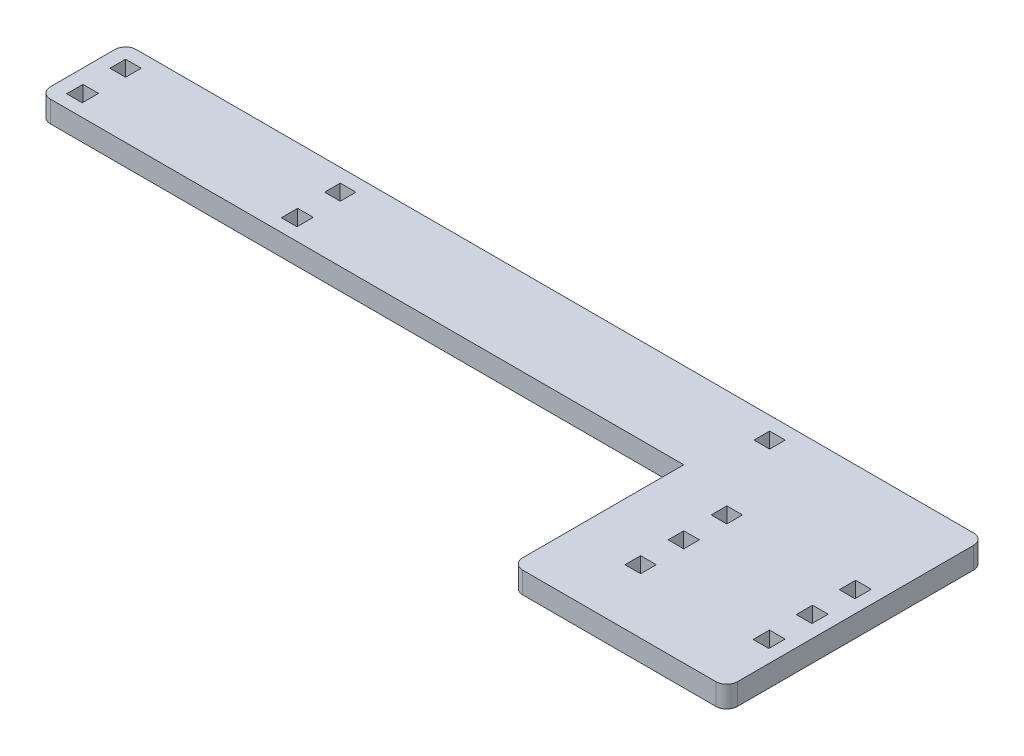
SolidWorks part; units mm, degrees
ref_plane "Front Plane" through (0, 0, 0) normal (0, 0, 1) x (1, 0, 0)
ref_plane "Top Plane" through (0, 0, 0) normal (0, 1, 0) x (1, 0, 0)
ref_plane "Right Plane" through (0, 0, 0) normal (1, 0, 0) x (0, 0, -1)
sketch "Sketch1" plane through (0, 0, 0) normal (0, 1, 0) x (1, 0, 0)
  line L0 (0, 0) -> (254, 0)
  line L1 (254, 0) -> (254, -76.2)
  line L2 (254, -76.2) -> (190.5, -76.2)
  line L3 (190.5, -76.2) -> (190.5, -25.4)
  line L4 (190.5, -25.4) -> (0, -25.4)
  line L5 (0, -25.4) -> (0, 0)
  line L6 (4.211, -16.8148) -> (8.8338, -16.8148)
  line L7 (4.064, -4.064) -> (8.6868, -4.064)
  line L8 (4.064, -4.064) -> (4.064, -8.6868)
  line L9 (4.064, -8.6868) -> (8.6868, -8.6868)
  line L10 (8.6868, -4.064) -> (8.6868, -8.6868)
  line L11 (4.211, -16.8148) -> (4.211, -21.6346)
  line L12 (4.211, -21.6346) -> (8.8338, -21.6346)
  line L13 (8.8338, -16.8148) -> (8.8338, -21.6346)
  line L14 (67.564, -4.064) -> (67.564, -8.6868)
  line L15 (67.564, -4.064) -> (72.1868, -4.064)
  line L16 (72.1868, -4.064) -> (72.1868, -8.6868)
  line L17 (67.564, -8.6868) -> (72.1868, -8.6868)
  line L18 (67.711, -16.8148) -> (72.3338, -16.8148)
  line L19 (72.3338, -16.8148) -> (72.3338, -21.6346)
  line L20 (67.711, -21.6346) -> (72.3338, -21.6346)
  line L21 (67.711, -16.8148) -> (67.711, -21.6346)
  line L30 (194.564, -4.064) -> (194.564, -8.6868)
  line L31 (194.564, -4.064) -> (199.1868, -4.064)
  line L32 (199.1868, -4.064) -> (199.1868, -8.6868)
  line L33 (194.564, -8.6868) -> (199.1868, -8.6868)
  line L46 (131.211, -16.8148) -> (135.8338, -16.8148) [skipped]
  line L47 (135.8338, -16.8148) -> (135.8338, -21.6346) [skipped]
  line L48 (131.211, -21.6346) -> (135.8338, -21.6346) [skipped]
  line L49 (131.211, -16.8148) -> (131.211, -21.6346) [skipped]
  line L50 (131.064, -4.064) -> (131.064, -8.6868) [skipped]
  line L51 (131.064, -8.6868) -> (135.6868, -8.6868) [skipped]
  line L52 (135.6868, -4.064) -> (135.6868, -8.6868) [skipped]
  line L53 (131.064, -4.064) -> (135.6868, -4.064) [skipped]
  line L58 (245.511, -29.5648) -> (250.1338, -29.5648)
  line L59 (250.1338, -29.5648) -> (250.1338, -34.3846)
  line L60 (245.511, -34.3846) -> (250.1338, -34.3846)
  line L61 (245.511, -29.5648) -> (245.511, -34.3846)
  line L66 (245.511, -42.3148) -> (250.1338, -42.3148)
  line L67 (250.1338, -42.3148) -> (250.1338, -47.1346)
  line L68 (245.511, -47.1346) -> (250.1338, -47.1346)
  line L69 (245.511, -42.3148) -> (245.511, -47.1346)
  line L74 (245.511, -55.0648) -> (250.1338, -55.0648)
  line L75 (250.1338, -55.0648) -> (250.1338, -59.8846)
  line L76 (245.511, -59.8846) -> (250.1338, -59.8846)
  line L77 (245.511, -55.0648) -> (245.511, -59.8846)
  line L86 (207.411, -29.5648) -> (212.0338, -29.5648)
  line L87 (212.0338, -29.5648) -> (212.0338, -34.1876)
  line L88 (207.411, -34.1876) -> (212.0338, -34.1876)
  line L89 (207.411, -29.5648) -> (207.411, -34.1876)
  line L90 (207.411, -42.3148) -> (212.0338, -42.3148)
  line L91 (212.0338, -42.3148) -> (212.0338, -46.9376)
  line L92 (207.411, -46.9376) -> (212.0338, -46.9376)
  line L93 (207.411, -42.3148) -> (207.411, -46.9376)
  line L94 (207.411, -55.0648) -> (212.0338, -55.0648)
  line L95 (212.0338, -55.0648) -> (212.0338, -59.6876)
  line L96 (207.411, -59.6876) -> (212.0338, -59.6876)
  line L97 (207.411, -55.0648) -> (207.411, -59.6876)
  line L110 (194.711, -16.8148) -> (199.3338, -16.8148) [skipped]
  line L111 (199.3338, -16.8148) -> (199.3338, -21.6346) [skipped]
  line L112 (194.711, -21.6346) -> (199.3338, -21.6346) [skipped]
  line L113 (194.711, -16.8148) -> (194.711, -21.6346) [skipped]
  point P15 (6.3754, -8.6868)
  dimension "D1" = 254
  dimension "D2" = 25.4
  dimension "D3" = 63.5
  dimension "D4" = 50.8
  dimension "D5" = 4.6228
  dimension "D6" = 4.6228
  dimension "D7" = 4.064
  dimension "D8" = 4.064
  dimension "D9" = 8.128
  dimension "D10" = 4
extrude "Boss-Extrude1" add sketch "Sketch1" along normal blind 6.35
fillet "Fillet2" radius 3.175 1 edges at (0, 3.175, 25.4)
fillet "Fillet3" radius 3.175 4 edges at (190.5, 3.175, 76.2) (254, 3.175, 76.2) (254, 3.175, 0) (0, 3.175, 0)
